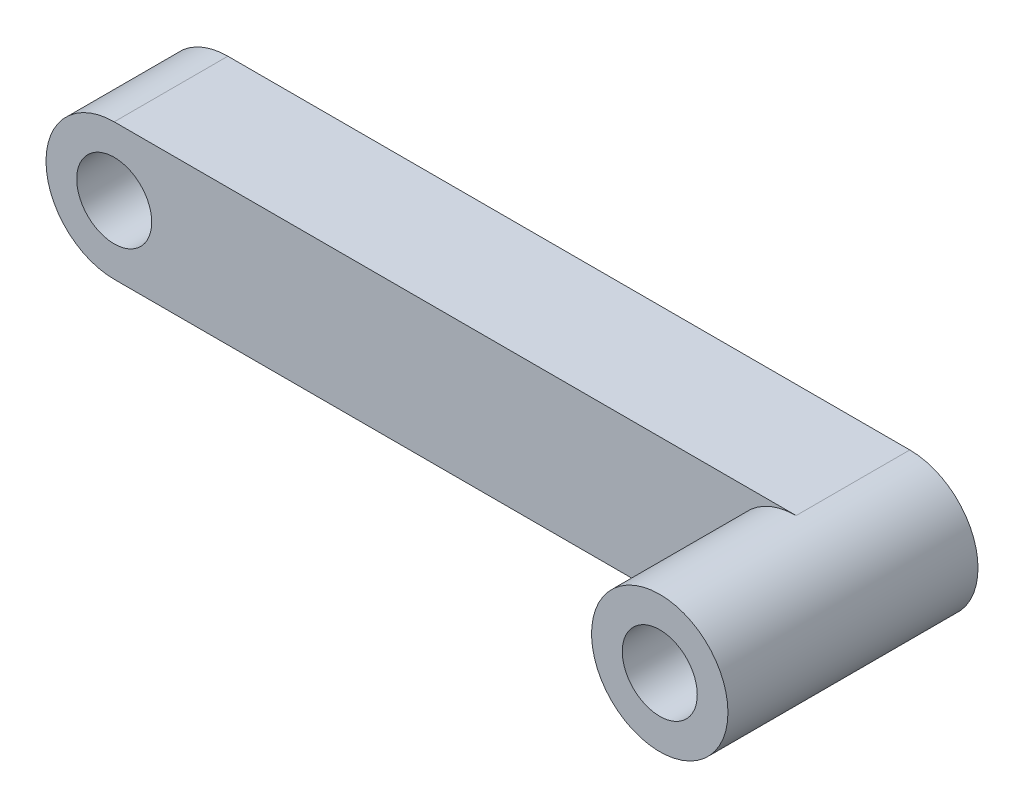
SolidWorks part; units mm, degrees
ref_plane "Ebene vorne" through (0, 0, 0) normal (0, 0, 1) x (1, 0, 0)
ref_plane "Ebene oben" through (0, 0, 0) normal (0, 1, 0) x (1, 0, 0)
ref_plane "Ebene rechts" through (0, 0, 0) normal (1, 0, 0) x (0, 0, -1)
sketch "Skizze1" plane through (0, 0, 0) normal (0, 0, 1) x (1, 0, 0)
  line L0 (-30, 3) -> (0, 3)
  line L1 (-30, 0) -> (0, 0) construction
  line L2 (-30, -3) -> (0, -3)
  circle A0 centre (0, 0) radius 1.65
  circle A1 centre (0, 0) radius 3
  circle A2 centre (-30, 0) radius 1.65
  circle A3 centre (-30, 0) radius 3
  dimension "D1" = 3.3
  dimension "D2" = 6
  dimension "D4" = 6
  dimension "D5" = 3.3
  dimension "D3" = 30
extrude "Aufsatz-Linear austragen1" add sketch "Skizze1" along normal blind 5
sketch "Skizze2" plane through (0, 0, 5) normal (0, 0, 1) x (1, 0, 0)
  circle A0 centre (0, 0) radius 1.65
  circle A1 centre (0, 0) radius 3
extrude "Aufsatz-Linear austragen2" add sketch "Skizze2" along normal blind 6
sketch "Skizze3" plane through (0, 0, 0) normal (0, 0, -1) x (-1, 0, 0)
  line L0 (0, 0) -> (45.5, 0) construction
